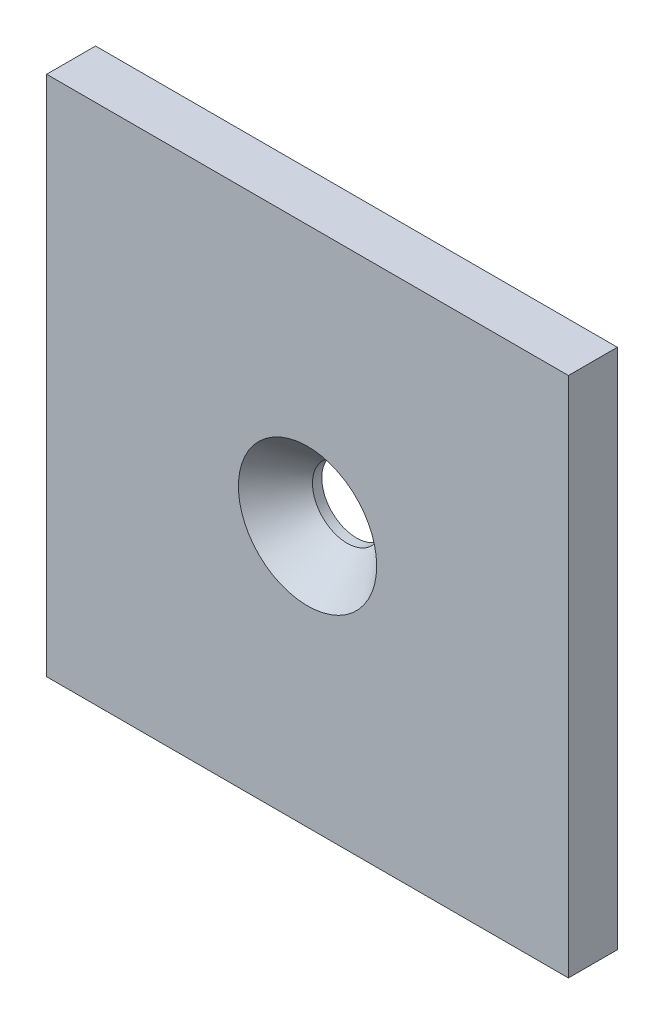
SolidWorks part; units mm, degrees
ref_plane "Front Plane" through (0, 0, 0) normal (0, 0, 1) x (1, 0, 0)
ref_plane "Top Plane" through (0, 0, 0) normal (0, 1, 0) x (1, 0, 0)
ref_plane "Right Plane" through (0, 0, 0) normal (1, 0, 0) x (0, 0, -1)
sketch "Sketch1" plane through (0, 0, 0) normal (0, 0, 1) x (1, 0, 0)
  line L1 (0, 0) -> (50.8, 0)
  line L2 (0, 0) -> (0, -50.8)
  line L3 (0, -50.8) -> (50.8, -50.8)
  line L4 (50.8, 0) -> (50.8, -50.8)
  point P6 (0, 0)
  dimension "D1" = 50.8
  dimension "D2" = 50.8
extrude "Boss-Extrude1" add sketch "Sketch1" along normal blind 4.7625
sketch "Sketch2" plane through (0, 0, 4.7625) normal (0, 0, 1) x (1, 0, 0)
  line L0 (50.8, 0) -> (0, 0) construction
  line L1 (0, 0) -> (0, -50.8) construction
  point P0 (25.4, -25.4)
  point P5 (33.7912, -25.5094)
  dimension "D1" = 25.4
  dimension "D2" = 25.4
hole_wizard "CSK for 1/4 Flat Head Machine Screw (100)1" positions "Sketch3" profile "Sketch4" countersink size "1/4" standard "ANSI Inch" end condition through all
sketch "Sketch3" plane through (0, 0, 4.7625) normal (0, 0, 1) x (1, 0, 0)
  point P0 (25.4, -25.4)
sketch "Sketch4" plane through (25.4, -25.4, 4.7625) normal (1, 0, 0) x (0, -1, 0)
  line L0 (0, 0) -> (0, 4.7625)
  line L1 (0, 4.7625) -> (3.3782, 4.7625)
  line L2 (3.3782, 4.7625) -> (3.3782, 3.857)
  line L3 (3.3782, 3.857) -> (6.731, 0)
  line L5 (6.731, 0) -> (0, 0)
  line L6 (-3.3782, 3.857) -> (-6.731, 0) construction
  line L11 (0, -6.35) -> (0, 107.95) construction
  dimension "Thru Hole Dia." = 6.7564
  dimension "Thru Hole Depth" = 4.7625
  dimension "Near C'Sink Dia." = 13.462
  dimension "Near C'Sink Angle" = 82
